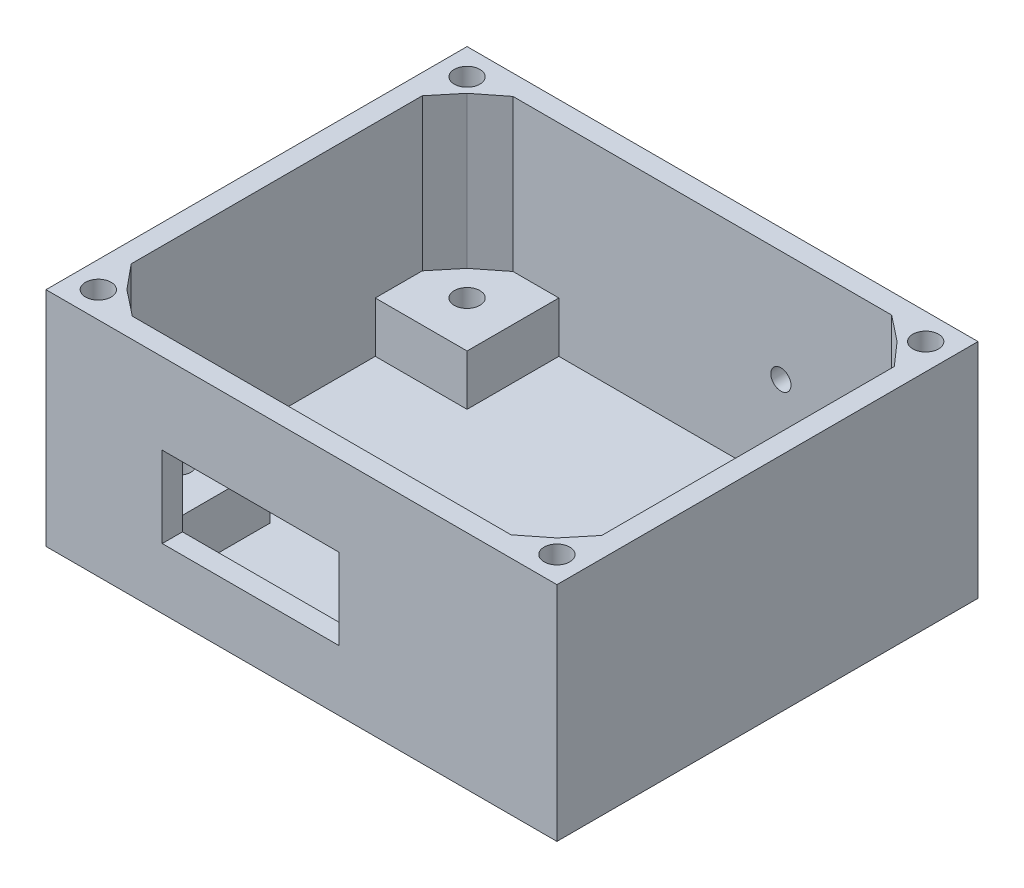
SolidWorks part; units mm, degrees
ref_plane "Front Plane" through (0, 0, 0) normal (0, 0, 1) x (1, 0, 0)
ref_plane "Top Plane" through (0, 0, 0) normal (0, 1, 0) x (1, 0, 0)
ref_plane "Right Plane" through (0, 0, 0) normal (1, 0, 0) x (0, 0, -1)
sketch "Sketch2" plane through (0, 0, 0) normal (0, 1, 0) x (1, 0, 0)
  line L0 (0, 0) -> (37.465, 0)
  line L1 (0, 0) -> (0, 28.575)
  line L2 (0, 28.575) -> (37.465, 28.575)
  line L3 (37.465, 28.575) -> (37.465, 0)
  line L4 (0, 0) -> (4.54, 0)
  line L5 (4.54, 0) -> (4.54, 4.54)
  line L6 (4.54, 4.54) -> (-4.54, 4.54)
  line L7 (-4.54, 4.54) -> (-4.54, -4.54)
  line L8 (-4.54, -4.54) -> (4.54, -4.54)
  line L9 (4.54, -4.54) -> (4.54, 0)
  line L10 (0, 28.575) -> (0, 24.035)
  line L11 (0, 24.035) -> (4.54, 24.035)
  line L12 (4.54, 24.035) -> (4.54, 33.115)
  line L13 (4.54, 33.115) -> (-4.54, 33.115)
  line L14 (-4.54, 33.115) -> (-4.54, 24.035)
  line L15 (-4.54, 24.035) -> (0, 24.035)
  line L16 (37.465, 28.575) -> (37.465, 24.035)
  line L17 (37.465, 24.035) -> (42.005, 24.035)
  line L18 (42.005, 24.035) -> (42.005, 33.115)
  line L19 (42.005, 33.115) -> (32.925, 33.115)
  line L20 (32.925, 33.115) -> (32.925, 24.035)
  line L21 (32.925, 24.035) -> (37.465, 24.035)
  line L22 (37.465, 0) -> (37.465, -4.54)
  line L23 (37.465, -4.54) -> (42.005, -4.54)
  line L24 (42.005, -4.54) -> (42.005, 4.54)
  line L25 (42.005, 4.54) -> (32.925, 4.54)
  line L26 (32.925, 4.54) -> (32.925, -4.54)
  line L27 (32.925, -4.54) -> (37.465, -4.54)
  line L28 (42.005, -4.54) -> (42.005, -6.54)
  line L29 (42.005, -4.54) -> (44.005, -4.54)
  line L30 (-4.54, -4.54) -> (-4.54, -6.54)
  line L31 (-4.54, -4.54) -> (-6.54, -4.54)
  line L32 (-4.54, 33.115) -> (-6.54, 33.115)
  line L33 (-4.54, 33.115) -> (-4.54, 35.115)
  line L34 (42.005, 33.115) -> (42.005, 35.115)
  line L35 (42.005, 33.115) -> (44.005, 33.115)
  line L36 (-4.54, -6.54) -> (42.005, -6.54)
  line L37 (42.005, -6.54) -> (44.005, -6.54)
  line L38 (44.005, -6.54) -> (44.005, -4.54)
  line L39 (44.005, -4.54) -> (44.005, 33.115)
  line L40 (44.005, 33.115) -> (44.005, 35.115)
  line L41 (44.005, 35.115) -> (42.005, 35.115)
  line L42 (42.005, 35.115) -> (-4.54, 35.115)
  line L43 (-4.54, 35.115) -> (-6.54, 35.115)
  line L44 (-6.54, 35.115) -> (-6.54, 33.115)
  line L45 (-6.54, 33.115) -> (-6.54, -4.54)
  line L46 (-6.54, -4.54) -> (-6.54, -6.54)
  line L47 (-6.54, -6.54) -> (-4.54, -6.54)
  line L48 (4.54, -4.54) -> (32.925, -4.54)
  line L49 (-4.54, 24.035) -> (-4.54, 4.54)
  line L50 (4.54, 33.115) -> (32.925, 33.115)
  line L51 (42.005, 24.035) -> (42.005, 4.54)
  circle A0 centre (0, 0) radius 1.27
  circle A1 centre (37.465, 0) radius 1.27
  circle A2 centre (0, 28.575) radius 1.27
  circle A3 centre (37.465, 28.575) radius 1.27
  dimension "D2" = 2.54
  dimension "D3" = 2.54
  dimension "D5" = 2.54
  dimension "D6" = 2.54
  dimension "D1" = 37.465
  dimension "D4" = 28.575
  dimension "D7" = 4.54
  dimension "D8" = 4.54
  dimension "D9" = 9.08
  dimension "D10" = 9.08
  dimension "D11" = 9.08
  dimension "D12" = 4.54
  dimension "D13" = 4.54
  dimension "D14" = 9.08
  dimension "D15" = 9.08
  dimension "D16" = 4.54
  dimension "D17" = 4.54
  dimension "D18" = 9.08
  dimension "D19" = 9.08
  dimension "D20" = 4.54
  dimension "D21" = 4.54
  dimension "D22" = 9.08
  dimension "D23" = 9.08
  dimension "D24" = 2
  dimension "D25" = 2
  dimension "D26" = 2
  dimension "D27" = 2
  dimension "D28" = 2
  dimension "D29" = 2
  dimension "D30" = 2
  dimension "D31" = 2
extrude "Boss-Extrude3" add sketch "Sketch2" along normal blind 20 contours L18 L51 L24 L29 L39 L35 | L37 L38 L29 L28 | L48 L8 L30 L36 L28 L23 L27 | L46 L47 L30 L31 | L49 L14 L32 L45 L31 L7 | L43 L44 L32 L33 | L13 L50 L19 L34 L42 L33 | L40 L41 L34 L35 | A3 L16 L17 L18 L19 L20 L2 | A3 L2 L20 L21 L16 | A1 L22 L23 L24 L25 L3 | A1 L3 L25 L26 L0 | A1 L0 L26 L27 L22 | A2 L1 L11 L12 L2 | A2 L2 L12 L13 L14 L15 L1 | A0 L4 L5 L6 L1 | A0 L1 L6 L7 L8 L9 L4
sketch "Sketch3" plane through (0, 20, 0) normal (0, 1, 0) x (1, 0, 0)
  line L1 (32.925, 24.035) -> (42.005, 24.035)
  line L2 (32.925, 24.035) -> (32.925, 33.115)
  line L3 (32.925, 33.115) -> (42.005, 33.115)
  line L4 (42.005, 24.035) -> (42.005, 33.115)
  dimension "D1" = 9.08
  dimension "D2" = 9.08
extrude "Cut-Extrude1" cut sketch "Sketch3" against normal blind 15
sketch "Sketch4" plane through (0, 20, 0) normal (0, 1, 0) x (1, 0, 0)
  line L1 (4.54, 24.035) -> (-4.54, 24.035)
  line L2 (4.54, 24.035) -> (4.54, 33.115)
  line L3 (4.54, 33.115) -> (-4.54, 33.115)
  line L4 (-4.54, 24.035) -> (-4.54, 33.115)
  dimension "D1" = 9.08
  dimension "D2" = 9.08
extrude "Cut-Extrude2" cut sketch "Sketch4" against normal blind 15
sketch "Sketch5" plane through (0, 20, 0) normal (0, 1, 0) x (1, 0, 0)
  line L1 (32.925, 4.54) -> (42.005, 4.54)
  line L2 (32.925, 4.54) -> (32.925, -4.54)
  line L3 (32.925, -4.54) -> (42.005, -4.54)
  line L4 (42.005, 4.54) -> (42.005, -4.54)
  dimension "D1" = 9.08
  dimension "D2" = 9.08
extrude "Cut-Extrude3" cut sketch "Sketch5" against normal blind 15
sketch "Sketch6" plane through (0, 20, 0) normal (0, 1, 0) x (1, 0, 0)
  line L1 (4.54, 4.54) -> (-4.54, 4.54)
  line L2 (4.54, 4.54) -> (4.54, -4.54)
  line L3 (4.54, -4.54) -> (-4.54, -4.54)
  line L4 (-4.54, 4.54) -> (-4.54, -4.54)
  dimension "D1" = 9.08
  dimension "D2" = 9.08
extrude "Cut-Extrude4" cut sketch "Sketch6" against normal blind 15
sketch "Sketch7" plane through (0, 0, 0) normal (0, -1, 0) x (1, 0, 0)
  line L1 (44.005, -35.115) -> (-6.54, -35.115)
  line L2 (44.005, -35.115) -> (44.005, 6.54)
  line L3 (44.005, 6.54) -> (-6.54, 6.54)
  line L4 (-6.54, -35.115) -> (-6.54, 6.54)
extrude "Boss-Extrude4" add sketch "Sketch7" along normal blind 2
sketch "Sketch9" plane through (0, 0, 6.54) normal (0, 0, 1) x (1, 0, 0)
  line L0 (-6.54, -2) -> (0.46, -2)
  line L1 (44.005, -2) -> (-6.54, -2) construction
  line L2 (0.46, -2) -> (0.46, 8)
  line L3 (0.46, 8) -> (22.46, 8)
  line L4 (0.46, 8) -> (3.46, 8)
  line L5 (22.46, 8) -> (22.46, 4)
  line L6 (22.46, 8) -> (22.46, 12)
  line L7 (3.46, 8) -> (4.96, 8)
  line L8 (4.96, 8) -> (4.96, 12)
  line L9 (3.46, 12) -> (22.46, 12)
  line L10 (4.96, 8) -> (4.96, 4)
  line L11 (4.96, 4) -> (22.46, 4)
  dimension "D1" = 7
  dimension "D2" = 10
  dimension "D3" = 22
  dimension "D4" = 3
  dimension "D5" = 4
  dimension "D6" = 4
  dimension "D7" = 1.5
extrude "Cut-Extrude8" cut sketch "Sketch9" against normal blind 10 contours L9 L8 L3 L6 | L10 L11 L5 L3
sketch "Sketch10" plane through (0, 5, 0) normal (0, 1, 0) x (1, 0, 0)
  line L0 (38.735, 0) -> (42.005, 0)
  line L1 (42.005, -4.54) -> (42.005, 4.54) construction
  line L2 (42.005, 0) -> (40.005, 0)
  line L3 (37.465, -1.27) -> (37.465, -4.54)
  line L4 (32.925, -4.54) -> (42.005, -4.54) construction
  line L5 (37.465, -4.54) -> (37.465, -2.54)
  line L6 (37.465, -2.54) -> (42.005, -2.54)
  line L7 (40.005, 0) -> (40.005, -2.54)
  line L8 (40.005, -2.54) -> (37.465, -4.54)
  line L9 (40.005, -2.54) -> (42.005, -0.108)
  circle A0 centre (37.465, 0) radius 1.27 construction
  line M3 (32.925, -4.54) -> (42.005, -4.54)
  line M4 (42.005, -4.54) -> (42.005, 4.54)
  dimension "D1" = 2
  dimension "D2" = 2
extrude "Boss-Extrude5" add sketch "Sketch10" along normal blind 15 contours L9 L6 M4 | L6 L8 M3 M4
sketch "Sketch11" plane through (0, 20, 0) normal (0, 1, 0) x (1, 0, 0)
  circle A0 centre (41.4192, -3.9542) radius 1.27
  dimension "D2" = 2.54
extrude "Cut-Extrude9" cut sketch "Sketch11" against normal blind 8
sketch "Sketch12" plane through (0, 20, 0) normal (0, 1, 0) x (1, 0, 0)
  line L0 (40.005, -2.54) -> (44.005, -6.54)
  line L1 (40.005, -2.54) -> (41.4192, -3.9542)
  line L2 (41.4192, -3.9542) -> (41.4192, -6.54)
  line L3 (-6.54, -6.54) -> (44.005, -6.54) construction
  line L4 (41.4192, -6.54) -> (44.005, -6.54)
  line L5 (41.4192, -3.9542) -> (44.005, -3.9542)
  line L6 (44.005, -6.54) -> (44.005, 35.115) construction
  line L7 (44.005, 35.115) -> (44.005, 32.525)
  line L8 (44.005, 35.115) -> (41.415, 35.115)
  line L9 (44.005, 35.115) -> (-6.54, 35.115) construction
  line L10 (41.415, 35.115) -> (41.415, 32.525)
  line L11 (44.005, 32.525) -> (41.415, 32.525)
  line L12 (44.005, 35.115) -> (40.0028, 31.1128)
  line L13 (42.005, -0.108) -> (44.005, -0.2659)
  line L14 (44.005, -0.2659) -> (44.005, -3.9542)
  line L15 (41.415, 35.115) -> (37.465, 35.115)
  line L16 (44.005, 32.525) -> (44.005, 28.835)
  line L17 (37.465, 35.115) -> (37.465, 33.115)
  line L18 (42.005, 33.115) -> (-4.54, 33.115) construction
  line L19 (37.465, -4.54) -> (37.465, -6.54)
  line L20 (37.465, -6.54) -> (41.4192, -6.54)
  line L21 (44.005, 28.835) -> (42.005, 28.835)
  line L22 (42.005, -0.108) -> (42.005, 33.115) construction
  line L23 (37.465, 33.115) -> (40.0028, 31.1128)
  line L24 (40.0028, 31.1128) -> (42.005, 28.835)
  circle A0 centre (41.415, 32.525) radius 1.27
  line M13 (-4.54, 33.115) -> (42.005, 33.115)
  line M14 (42.005, 33.115) -> (42.005, -0.108)
  dimension "D14" = 2.54
  dimension "D1" = 2.5858
  dimension "D2" = 2.5858
  dimension "D3" = 5.6569
  dimension "D4" = 2.59
  dimension "D5" = 2.59
  dimension "D6" = 2.59
  dimension "D7" = 5.66
  dimension "D8" = 3.6883
  dimension "D9" = 3.95
  dimension "D10" = 3.69
  dimension "D11" = 3.9542
  dimension "D12" = 6.54
  dimension "D13" = 6.54
extrude "Boss-Extrude9" add sketch "Sketch12" against normal blind 18 contours A0 L23 L12 M13 | A0 L12 L24 M14 | L12 L11 M14 | L12 L10 M13 | L12 A0 L11 M14 | A0 L12 L10 M13
sketch "Sketch17" plane through (0, 20, 0) normal (0, 1, 0) x (1, 0, 0)
  line L0 (44.005, 35.115) -> (40.0028, 31.1128)
  line L1 (40.0028, 31.1128) -> (41.417, 32.527)
  circle A0 centre (41.417, 32.527) radius 1.27
  dimension "D2" = 2.54
  dimension "D1" = 2
extrude "Cut-Extrude12" cut sketch "Sketch17" against normal blind 8 contours L0 A0 | L0 A0
sketch "Sketch18" plane through (0, 20, 0) normal (0, 1, 0) x (1, 0, 0)
  line L0 (37.465, -4.54) -> (37.465, -6.54)
  line L1 (-6.54, -6.54) -> (44.005, -6.54) construction
  line L2 (42.005, -0.108) -> (44.005, -0.108)
  line L3 (44.005, -6.54) -> (44.005, 35.115) construction
  line L4 (-6.54, -6.54) -> (-6.54, -0.11)
  line L5 (-6.54, 35.115) -> (-6.54, -6.54) construction
  line L6 (-6.54, -6.54) -> (0, -6.54)
  line L7 (-6.54, -0.11) -> (-4.54, -0.11)
  line L8 (-4.54, 4.54) -> (-4.54, -4.54) construction
  line L9 (0, -6.54) -> (0, -4.54)
  line L12 (-6.54, -6.54) -> (-2.5378, -2.5378)
  line L13 (44.005, -6.54) -> (40.005, -2.54)
  line L14 (-4.54, -0.11) -> (-2.5378, -2.5378)
  line L15 (0, -4.54) -> (-2.5378, -2.5378)
  line M9 (37.465, -4.54) -> (-4.54, -4.54)
  line M10 (-4.54, -4.54) -> (-4.54, 33.115)
  dimension "D1" = 6.54
  dimension "D2" = 6.432
  dimension "D3" = 6.43
  dimension "D4" = 6.54
  dimension "D5" = 5.66
extrude "Boss-Extrude10" add sketch "Sketch18" against normal blind 18 contours L14 L12 M10 | L15 L12 M9
sketch "Sketch19" plane through (0, 20, 0) normal (0, 1, 0) x (1, 0, 0)
  line L0 (-6.54, -6.54) -> (-2.5378, -2.5378)
  line L1 (-2.5378, -2.5378) -> (-3.952, -3.952)
  circle A0 centre (-3.952, -3.952) radius 1.27
  dimension "D2" = 2.54
  dimension "D1" = 2
extrude "Cut-Extrude13" cut sketch "Sketch19" against normal blind 8 contours L0 A0 | L0 A0
sketch "Sketch20" plane through (0, 20, 0) normal (0, 1, 0) x (1, 0, 0)
  line L0 (37.465, -4.54) -> (37.465, -6.54)
  line L1 (-6.54, -6.54) -> (44.005, -6.54) construction
  line L2 (42.005, -0.108) -> (44.005, -0.108)
  line L3 (44.005, -6.54) -> (44.005, 35.115) construction
  line L4 (-6.54, 35.115) -> (-6.54, 28.685)
  line L5 (-6.54, 35.115) -> (-6.54, -6.54) construction
  line L6 (-6.54, 35.115) -> (0, 35.115)
  line L7 (44.005, 35.115) -> (-6.54, 35.115) construction
  line L8 (-6.54, 28.685) -> (-4.54, 28.685)
  line L9 (-4.54, 33.115) -> (-4.54, -0.11) construction
  line L10 (0, 35.115) -> (0, 33.115)
  line L13 (-6.54, 35.115) -> (-2.5378, 31.1128)
  line L14 (-4.54, 28.685) -> (-2.5378, 31.1128)
  line L15 (-2.5378, 31.1128) -> (0, 33.115)
  line M8 (-4.54, -0.11) -> (-4.54, 33.115)
  line M9 (-4.54, 33.115) -> (37.465, 33.115)
  dimension "D1" = 6.432
  dimension "D2" = 6.54
  dimension "D3" = 6.43
  dimension "D4" = 6.54
  dimension "D5" = 5.66
extrude "Boss-Extrude11" add sketch "Sketch20" against normal blind 18 contours L13 L15 M9 | L14 L13 M8
sketch "Sketch21" plane through (0, 20, 0) normal (0, 1, 0) x (1, 0, 0)
  line L0 (-6.54, 35.115) -> (-2.5378, 31.1128)
  line L1 (-2.5378, 31.1128) -> (-3.952, 32.527)
  circle A0 centre (-3.952, 32.527) radius 1.27
  dimension "D1" = 5.66
  dimension "D2" = 2
extrude "Cut-Extrude14" cut sketch "Sketch21" against normal blind 8 contours L0 A0 | L0 A0
sketch "Sketch22" plane through (0, 0, -35.115) normal (0, 0, -1) x (-1, 0, 0)
  line L0 (-44.005, -2) -> (-26.505, -2)
  line L1 (6.54, -2) -> (-44.005, -2) construction
  line L2 (-26.505, -2) -> (-26.505, 9)
  circle A0 centre (-26.505, 9) radius 1
  dimension "D1" = 17.5
  dimension "D2" = 11
extrude "Cut-Extrude16" cut sketch "Sketch22" against normal blind 8 contours A0
sketch "Sketch23" plane through (0, 20, 0) normal (0, 1, 0) x (1, 0, 0)
  line L0 (40.0028, 31.1128) -> (44.005, 35.115)
  line L1 (41.417, 32.527) -> (41.417, 35.115)
  line L2 (44.005, 35.115) -> (-6.54, 35.115) construction
  line L3 (41.417, 32.527) -> (44.005, 32.527)
  line L4 (44.005, -6.54) -> (44.005, 35.115) construction
